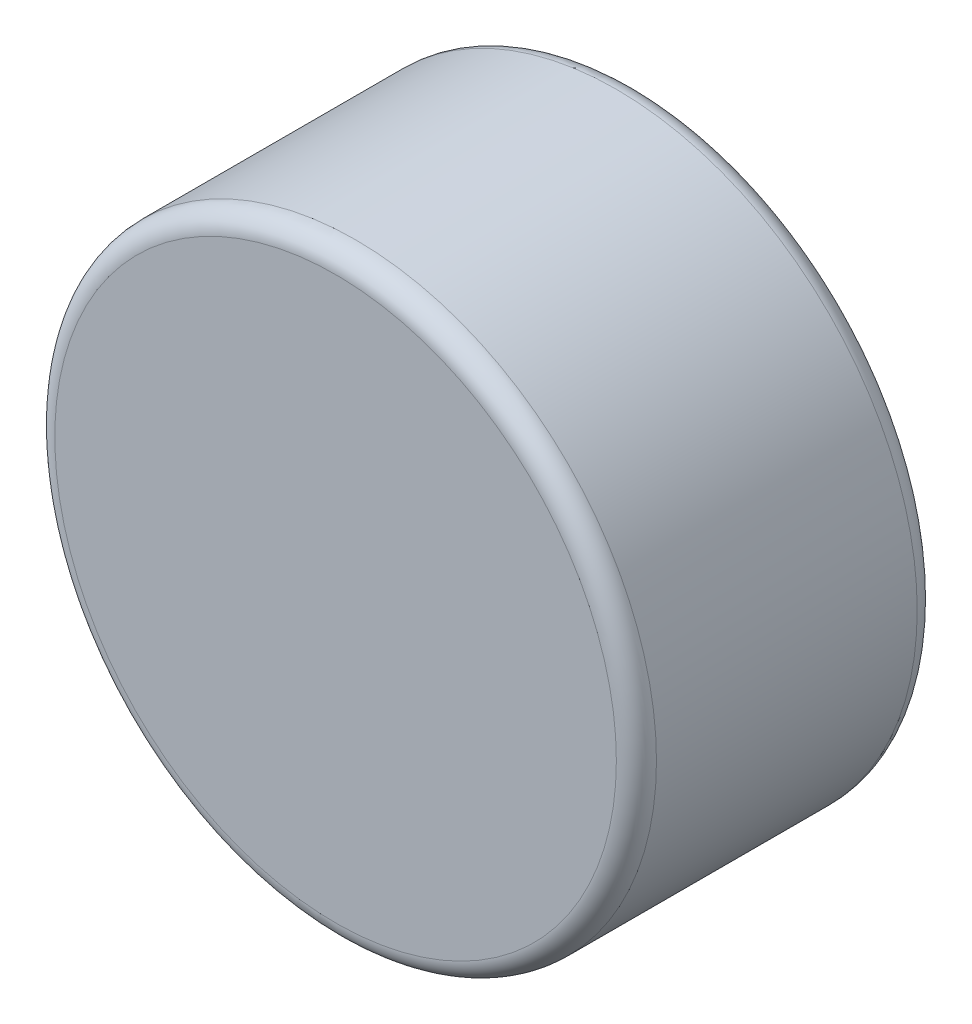
SolidWorks part; units mm, degrees
ref_plane "前视基准面" through (0, 0, 0) normal (0, 0, 1) x (1, 0, 0)
ref_plane "上视基准面" through (0, 0, 0) normal (0, 1, 0) x (1, 0, 0)
ref_plane "右视基准面" through (0, 0, 0) normal (1, 0, 0) x (0, 0, -1)
other "Configuration Table"
sketch "草图1" plane through (0, 0, 0) normal (0, 0, 1) x (1, 0, 0)
  circle A0 centre (0, 0) radius 3
  dimension "D1" = 6
extrude "凸台-拉伸1" add sketch "草图1" along normal blind 3
fillet "圆角1" radius 0.2 2 edges at (3, 0, 0) (3, 0, 3)
